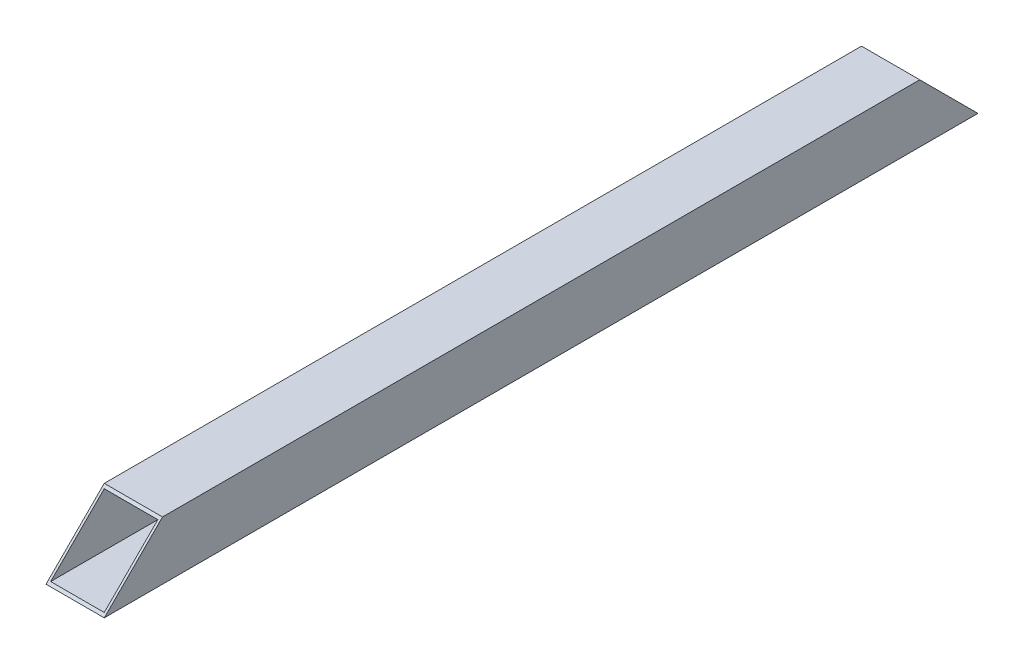
SolidWorks part; units mm, degrees
ref_plane "Alzado" through (0, 0, 0) normal (0, 0, 1) x (1, 0, 0)
ref_plane "Planta" through (0, 0, 0) normal (0, 1, 0) x (1, 0, 0)
ref_plane "Vista lateral" through (0, 0, 0) normal (1, 0, 0) x (0, 0, -1)
sketch "Croquis1" plane through (0, 0, 0) normal (0, 0, 1) x (1, 0, 0)
  line L1 (-69.6345, 59.7691) -> (30.3655, 59.7691)
  line L2 (-69.6345, 59.7691) -> (-69.6345, -40.2309)
  line L3 (-69.6345, -40.2309) -> (30.3655, -40.2309)
  line L4 (30.3655, 59.7691) -> (30.3655, -40.2309)
  line L5 (-65.6345, 55.7691) -> (26.3655, 55.7691)
  line L6 (-65.6345, 55.7691) -> (-65.6345, -36.2309)
  line L7 (-65.6345, -36.2309) -> (26.3655, -36.2309)
  line L8 (26.3655, 55.7691) -> (26.3655, -36.2309)
  dimension "D1" = 100
  dimension "D2" = 100
  dimension "D3" = 4
  dimension "D4" = 4
  dimension "D5" = 4
  dimension "D6" = 4
extrude "Saliente-Extruir2" add sketch "Croquis1" along normal blind 1500
sketch "Croquis2" plane through (-69.6345, 0, 0) normal (-1, 0, 0) x (0, 0, 1)
  line L0 (1500, -40.2309) -> (1400, 59.7691)
  line L1 (1500, 59.7691) -> (0, 59.7691) construction
  line L2 (1400, 59.7691) -> (1500, 59.7691)
  line L3 (1500, 59.7691) -> (1500, -40.2309)
  line L4 (0, -40.2309) -> (100, 59.7691)
  line L5 (0, 59.7691) -> (0, -40.2309) construction
  line L6 (0, -40.2309) -> (0, 59.7691)
  line L7 (0, 59.7691) -> (100, 59.7691)
  dimension "D1" = 45
extrude "Cortar-Extruir2" cut sketch "Croquis2" against normal blind 180
